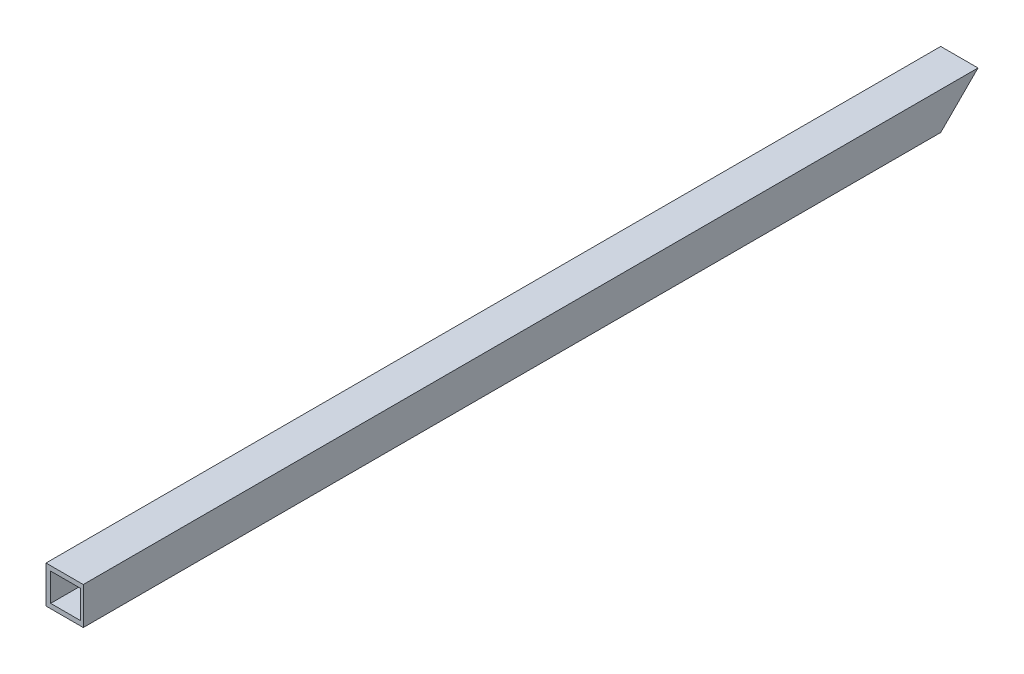
SolidWorks part; units mm, degrees
ref_plane "Front Plane" through (0, 0, 0) normal (0, 0, 1) x (1, 0, 0)
ref_plane "Top Plane" through (0, 0, 0) normal (0, 1, 0) x (1, 0, 0)
ref_plane "Right Plane" through (0, 0, 0) normal (1, 0, 0) x (0, 0, -1)
sketch "Sketch1" plane through (0, 0, 0) normal (0, 0, 1) x (1, 0, 0)
  line L1 (0, 0) -> (25.4, 0)
  line L2 (0, 0) -> (0, 25.4)
  line L3 (0, 25.4) -> (25.4, 25.4)
  line L4 (25.4, 0) -> (25.4, 25.4)
  dimension "D1" = 25.4
  dimension "D2" = 25.4
extrude "Boss-Extrude2" add sketch "Sketch1" along normal blind 609.6 contours L3 L4 L1 L2
sketch "Sketch2" plane through (0, 0, 0) normal (0, 0, -1) x (-1, 0, 0)
  line L0 (-23.4778, 22.225) -> (-3.175, 22.225)
  line L1 (-23.4778, 22.225) -> (-23.4778, 3.175)
  line L2 (-23.4778, 3.175) -> (-3.175, 3.175)
  line L3 (-3.175, 22.225) -> (-3.175, 3.175)
  line L4 (0, 0) -> (0, 25.4) construction
  line L5 (0, 0) -> (-25.4, 0) construction
  dimension "D1" = 3.175
  dimension "D2" = 3.175
extrude "Cut-Extrude1" cut sketch "Sketch2" against normal through all
sketch "Sketch3" plane through (25.4, 0, 0) normal (1, 0, 0) x (0, 0, -1)
  line L0 (0, 25.4) -> (-25.4, 0)
  line L1 (0, 0) -> (0, 25.4) construction
  line L2 (-609.6, 0) -> (0, 0) construction
  line L3 (-25.4, 0) -> (0, 0)
  line L4 (0, 0) -> (0, 25.4)
  dimension "D1" = 45
extrude "Cut-Extrude2" cut sketch "Sketch3" against normal through all
